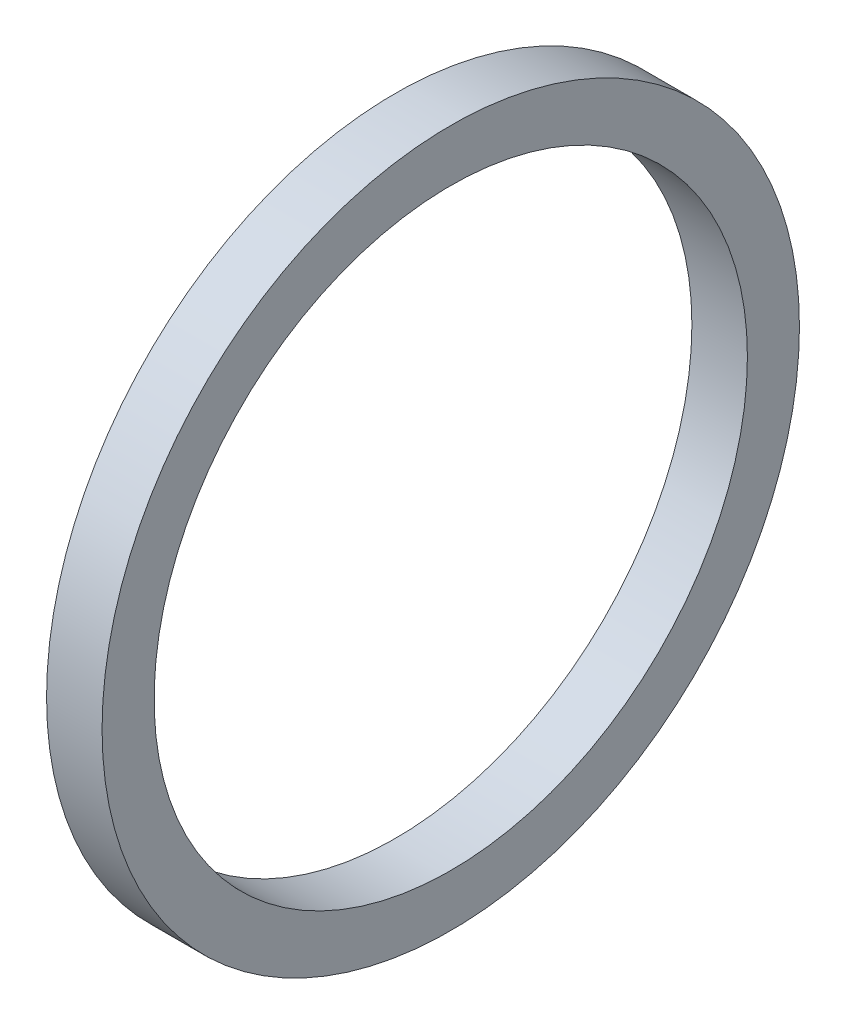
SolidWorks part; units mm, degrees
ref_plane "Front Plane" through (0, 0, 0) normal (0, 0, 1) x (1, 0, 0)
ref_plane "Top Plane" through (0, 0, 0) normal (0, 1, 0) x (1, 0, 0)
ref_plane "Right Plane" through (0, 0, 0) normal (1, 0, 0) x (0, 0, -1)
sketch "Sketch1" plane through (0, 0, 0) normal (1, 0, 0) x (0, 0, -1)
  circle A0 centre (0, 0) radius 20.1
  dimension "D1" = 40.2
extrude "Extrude-Thin1" add sketch "Sketch1" along normal blind 3.2 thin thin type one direction reverse wall 3
